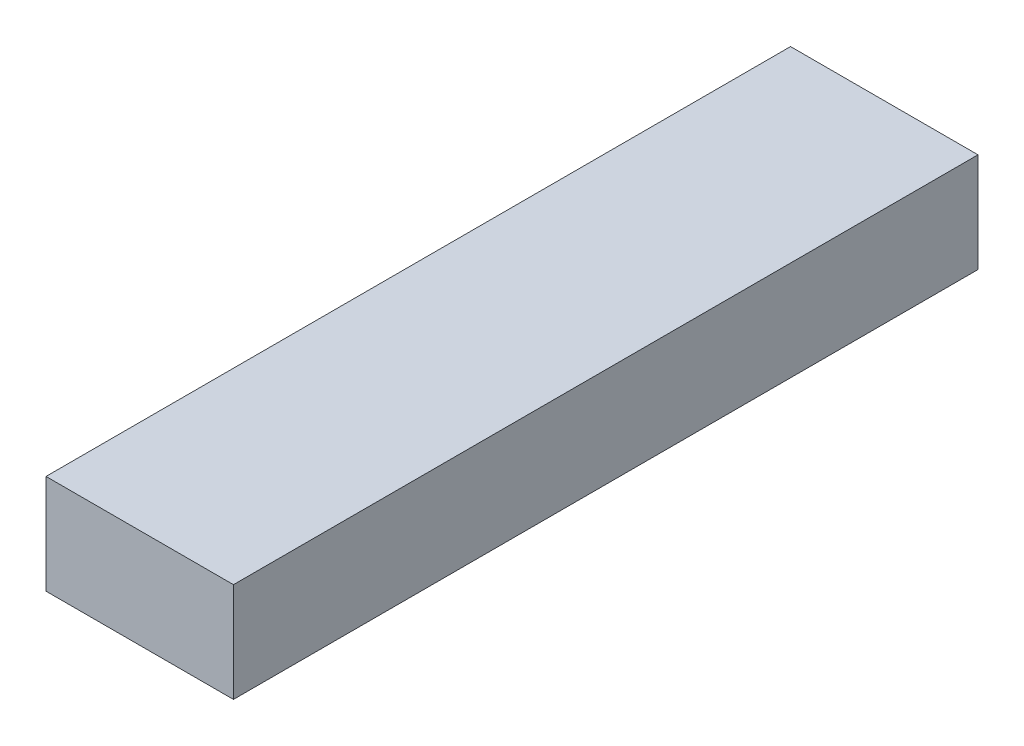
SolidWorks part; units mm, degrees
ref_plane "Front Plane" through (0, 0, 0) normal (0, 0, 1) x (1, 0, 0)
ref_plane "Top Plane" through (0, 0, 0) normal (0, 1, 0) x (1, 0, 0)
ref_plane "Right Plane" through (0, 0, 0) normal (1, 0, 0) x (0, 0, -1)
sketch "Sketch1" plane through (0, 0, 0) normal (0, 0, 1) x (1, 0, 0)
  line L1 (0, 0) -> (88.1254, 0)
  line L2 (0, 0) -> (0, 46.7297)
  line L3 (0, 46.7297) -> (88.1254, 46.7297)
  line L4 (88.1254, 0) -> (88.1254, 46.7297)
  dimension "D1" = 88.1254
  dimension "D2" = 46.7297
extrude "Boss-Extrude1" add sketch "Sketch1" along normal blind 350
